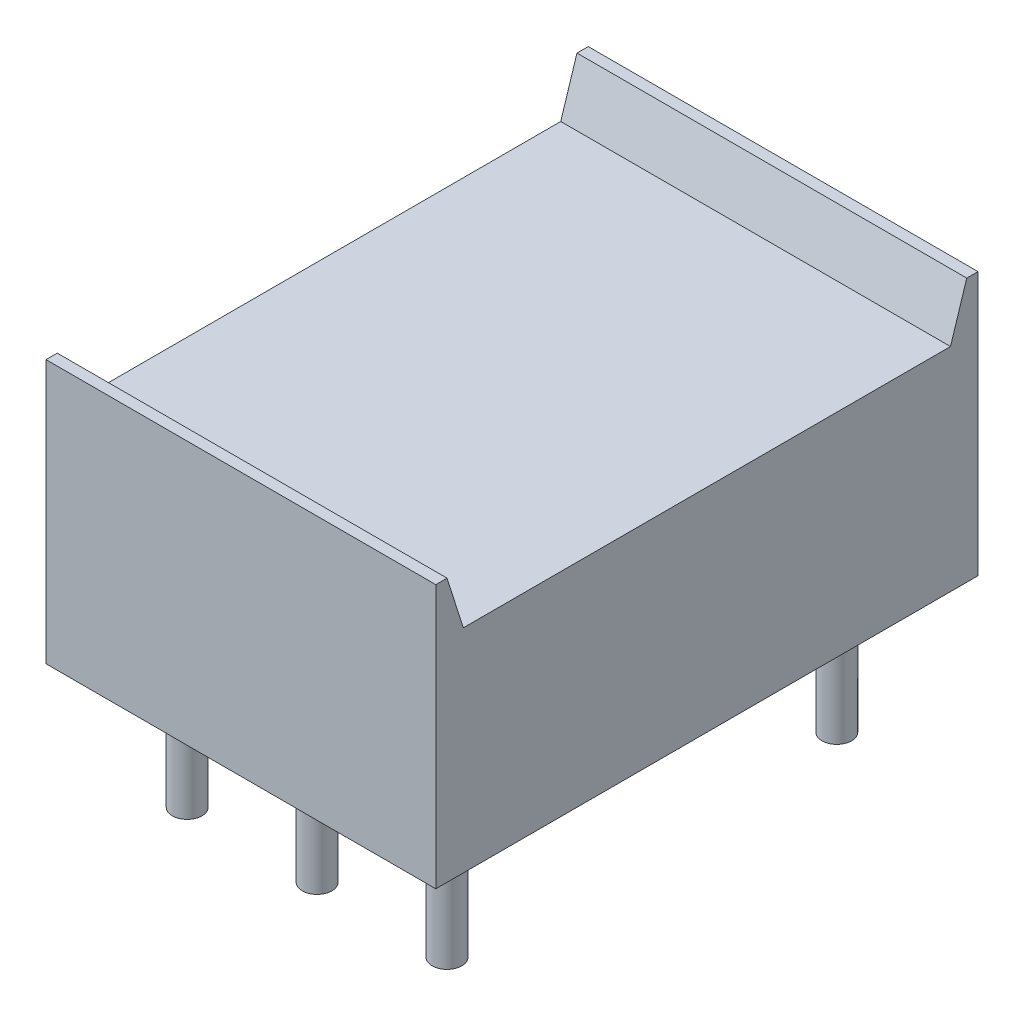
SolidWorks part; units mm, degrees
ref_plane "Front Plane" through (0, 0, 0) normal (0, 0, 1) x (1, 0, 0)
ref_plane "Top Plane" through (0, 0, 0) normal (0, 1, 0) x (1, 0, 0)
ref_plane "Right Plane" through (0, 0, 0) normal (1, 0, 0) x (0, 0, -1)
sketch "Sketch1" plane through (0, 0, 0) normal (0, 1, 0) x (1, 0, 0)
  line L1 (-3.81, -5.3) -> (3.81, -5.3)
  line L2 (-3.81, -5.3) -> (-3.81, 5.3)
  line L3 (-3.81, 5.3) -> (3.81, 5.3)
  line L4 (3.81, -5.3) -> (3.81, 5.3)
  line L5 (-3.81, -5.3) -> (3.81, 5.3) construction
  line L6 (-3.81, 5.3) -> (3.81, -5.3) construction
  point P0 (0, 0)
  dimension "D1" = 10.6
  dimension "D2" = 7.62
extrude "Boss-Extrude1" add sketch "Sketch1" along normal blind 5.15
sketch "Sketch3" plane through (0, 0, 0) normal (0, -1, 0) x (1, 0, 0)
  line L1 (-2.54, 3.81) -> (2.54, 3.81) construction
  line L2 (-2.54, 3.81) -> (-2.54, -3.81) construction
  line L3 (-2.54, -3.81) -> (2.54, -3.81) construction
  line L4 (2.54, 3.81) -> (2.54, -3.81) construction
  line L5 (-2.54, 3.81) -> (2.54, -3.81) construction
  line L6 (-2.54, -3.81) -> (2.54, 3.81) construction
  circle A0 centre (2.54, -3.81) radius 0.29
  point P0 (0, 0)
  dimension "D3" = 0.58
  dimension "D1" = 5.08
  dimension "D2" = 7.62
extrude "Boss-Extrude2" add sketch "Sketch3" along normal blind 2.54
pattern_linear "LPattern1" count 3 spacing 2.54 along (-1, 0, 0) count 2 spacing 7.62 along (0, 0, 1) of "Boss-Extrude2"
sketch "Sketch4" plane through (-3.81, 0, 0) normal (-1, 0, 0) x (0, 0, 1)
  line L0 (-5.08, 5.15) -> (-4.7625, 4.15)
  line L1 (-5.3, 5.15) -> (5.3, 5.15) construction
  line L2 (-4.7625, 4.15) -> (4.7625, 4.15)
  line L3 (4.7625, 4.15) -> (5.08, 5.15)
  line L4 (5.08, 5.15) -> (-5.08, 5.15)
  line L5 (0, 0) -> (0, 4.15) construction
  line L6 (0, 4.15) -> (0, 5.15) construction
  dimension "D1" = 9.525
  dimension "D2" = 10.16
  dimension "D3" = 1
extrude "Cut-Extrude1" cut sketch "Sketch4" against normal through all
